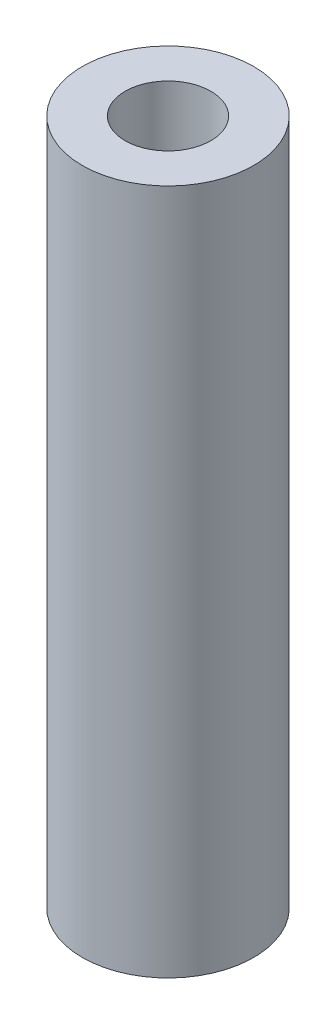
SolidWorks part; units mm, degrees
ref_plane "前视基准面" through (0, 0, 0) normal (0, 0, 1) x (1, 0, 0)
ref_plane "上视基准面" through (0, 0, 0) normal (0, 1, 0) x (1, 0, 0)
ref_plane "右视基准面" through (0, 0, 0) normal (1, 0, 0) x (0, 0, -1)
other "Configuration Table"
sketch "草图1" plane through (0, 0, 0) normal (0, 1, 0) x (1, 0, 0)
  circle A0 centre (0, 0) radius 3
  circle A1 centre (0, 0) radius 1.5
  dimension "D1" = 6
  dimension "D2" = 3
extrude "凸台-拉伸1" add sketch "草图1" along normal blind 24
